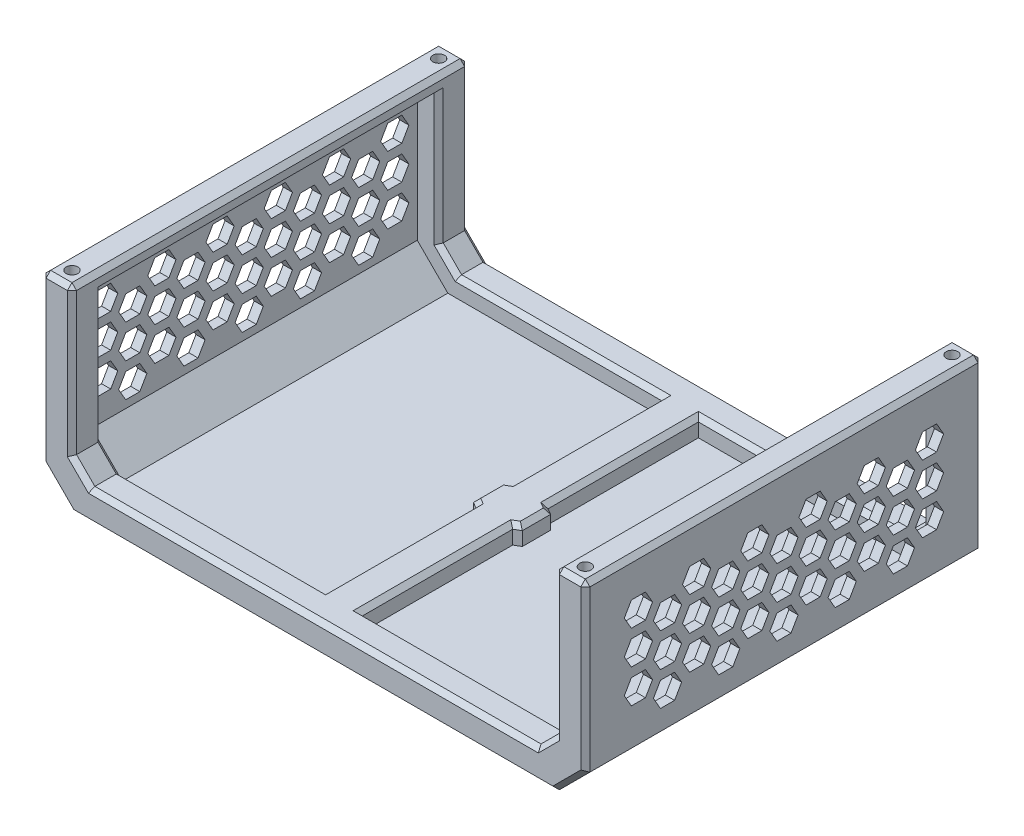
SolidWorks part; units mm, degrees
other "标注1"
sketch "草图16" plane through (-89, 60, 130) normal (-0.0084, 0.3052, 0.9522) x (0.9895, -0.1352, 0.0521)
ref_plane "前视基准面" through (0, 0, 0) normal (0, 0, 1) x (1, 0, 0)
ref_plane "上视基准面" through (0, 0, 0) normal (0, 1, 0) x (1, 0, 0)
ref_plane "右视基准面" through (0, 0, 0) normal (1, 0, 0) x (0, 0, -1)
sketch "草图1" plane through (0, 0, 0) normal (0, 0, 1) x (1, 0, 0)
  line L0 (-86, 0) -> (86, 0)
  line L1 (86, 0) -> (86, 60)
  line L2 (86, 60) -> (89, 60)
  line L3 (89, 60) -> (89, -4)
  line L4 (89, -4) -> (-89, -4)
  line L5 (0, -4) -> (0, 0) construction
  line L6 (-89, 60) -> (-89, -4)
  line L7 (-86, 60) -> (-89, 60)
  line L8 (-86, 0) -> (-86, 60)
  dimension "D1" = 3
  dimension "D2" = 4
  dimension "D3" = 178
  dimension "D4" = 60
extrude "凸台-拉伸2" add sketch "草图1" along normal blind 130
sketch "草图3" plane through (0, 60, 0) normal (0, 1, 0) x (1, 0, 0)
  line L0 (89, -130) -> (86, -130) construction
  line L1 (-79, -10) -> (-89, -10)
  line L2 (-79, -10) -> (-79, 0)
  line L3 (-79, 0) -> (-89, 0)
  line L4 (-89, -10) -> (-89, 0)
  line L5 (-79, -10) -> (-89, 0) construction
  line L6 (-79, 0) -> (-89, -10) construction
  line L7 (79, -10) -> (89, -10)
  line L8 (79, -10) -> (79, 0)
  line L9 (79, 0) -> (89, 0)
  line L10 (89, -10) -> (89, 0)
  line L11 (79, -10) -> (89, 0) construction
  line L12 (79, 0) -> (89, -10) construction
  line L13 (79, -120) -> (89, -120)
  line L14 (79, -120) -> (79, -130)
  line L15 (79, -130) -> (89, -130)
  line L16 (89, -120) -> (89, -130)
  line L17 (79, -120) -> (89, -130) construction
  line L18 (79, -130) -> (89, -120) construction
  line L19 (89, -130) -> (89, 0) construction
  line L21 (-79, -120) -> (-89, -120)
  line L22 (-79, -120) -> (-79, -130)
  line L23 (-79, -130) -> (-89, -130)
  line L24 (-89, -120) -> (-89, -130)
  line L25 (-79, -120) -> (-89, -130) construction
  line L26 (-79, -130) -> (-89, -120) construction
  point P0 (-84, -5)
  point P6 (84, -125)
  point P7 (84, -5)
  point P21 (-84, -125)
  dimension "D1" = 10
  dimension "D2" = 10
  dimension "D3" = 10
  dimension "D4" = 10
  dimension "D5" = 10
  dimension "D6" = 10
  dimension "D7" = 10
  dimension "D8" = 10
extrude "凸台-拉伸3" add sketch "草图3" against normal up to surface (60 mm away) up to face at (0, 0, 65)
sketch "草图4" plane through (0, 60, 0) normal (0, 1, 0) x (1, 0, 0)
  line L0 (-79, 0) -> (-89, 0) construction
  line L1 (-89, -130) -> (-89, 0) construction
  line L2 (89, 0) -> (79, 0) construction
  line L3 (89, -130) -> (89, 0) construction
  line L4 (89, -130) -> (79, -130) construction
  line L5 (-79, -130) -> (-89, -130) construction
  circle A0 centre (-84, -5) radius 1.9
  circle A1 centre (84, -5) radius 1.9
  circle A2 centre (84, -125) radius 1.9
  circle A3 centre (-84, -125) radius 1.9
  dimension "D4" = 5
  dimension "D9" = 3.8
  dimension "D10" = 3.8
  dimension "D11" = 3.8
  dimension "D12" = 3.8
  dimension "D1" = 5
  dimension "D2" = 5
  dimension "D3" = 5
  dimension "D5" = 5
  dimension "D6" = 5
  dimension "D7" = 5
  dimension "D8" = 5
extrude "切除-拉伸1" cut sketch "草图4" against normal blind 8
chamfer "倒角1" distance 10 angle 45 2 edges at (86, 0, 65) (-86, 0, 65)
chamfer "倒角2" distance 10 angle 45 2 edges at (89, -4, 65) (-89, -4, 65)
sketch "草图6" plane through (0, 0, 0) normal (1, 0, 0) x (0, 0, -1)
  line L1 (-120, 6) -> (-130, 6)
  line L2 (-120, 6) -> (-120, -4)
  line L3 (-120, -4) -> (-130, -4)
  line L4 (-130, 6) -> (-130, -4)
  line L5 (-120, 6) -> (-130, -4) construction
  line L6 (-120, -4) -> (-130, 6) construction
  line L7 (-10, 6) -> (0, 6)
  line L8 (-10, 6) -> (-10, -4)
  line L9 (-10, -4) -> (0, -4)
  line L10 (0, 6) -> (0, -4)
  line L11 (-10, 6) -> (0, -4) construction
  line L12 (-10, -4) -> (0, 6) construction
  point P0 (-125, 1)
  point P6 (-5, 1)
  dimension "D1" = 10
  dimension "D2" = 10
  dimension "D3" = 10
  dimension "D4" = 10
extrude "凸台-拉伸4" add sketch "草图6" along normal up to surface and the other way up to surface up to face at (79, 31.5, 125) other way up to face at (-79, 31.5, 125)
chamfer "倒角3" distance 6 angle 45 4 edges at (-79, 6, 5) (79, 6, 5) (79, 6, 125) (-79, 6, 125)
sketch "草图10" plane through (0, 0, 10) normal (0, 0, 1) x (1, 0, 0)
  line L0 (86, 60) -> (79, 60)
  line L1 (79, 60) -> (86, 60) construction
  line L2 (79, 60) -> (79, 55)
  line L3 (79, 12) -> (79, 60) construction
  line L4 (79, 55) -> (86, 50)
  line L5 (86, 60) -> (86, 10) construction
  line L6 (86, 50) -> (86, 60)
  line L7 (-86, 60) -> (-79, 60)
  line L8 (-86, 60) -> (-79, 60) construction
  line L9 (-79, 12) -> (-79, 60) construction
  line L10 (-79, 60) -> (-79, 56)
  line L11 (-79, 56) -> (-86, 50)
  line L12 (-86, 10) -> (-86, 60) construction
  line L13 (-86, 50) -> (-86, 60)
  dimension "D1" = 5
  dimension "D2" = 10
  dimension "D3" = 10
  dimension "D4" = 4
extrude "凸台-拉伸6" add sketch "草图10" along normal up to next
sketch "草图17" plane through (0, 0, 0) normal (0, 1, 0) x (1, 0, 0)
  line L0 (73, -10) -> (-73, -10) construction
  line L1 (-6, -10) -> (6, -10)
  line L2 (-6, -10) -> (-6, -120)
  line L3 (-6, -120) -> (6, -120)
  line L4 (6, -10) -> (6, -120)
  line L5 (73, -120) -> (-73, -120) construction
  line L6 (0, 0) -> (0, -130) construction
  line L7 (73, 0) -> (-73, 0) construction
  line L8 (73, -130) -> (-73, -130) construction
  line L13 (-76, -10) -> (76, -10) construction
  point P14 (4.0636, -10)
  point P17 (0, -10)
  dimension "D1" = 12
extrude "凸台-拉伸7" add sketch "草图17" along normal up to surface (6 mm away) up to face at (0, 6, 5)
sketch "草图20" plane through (0, -4, 0) normal (0, -1, 0) x (-1, 0, 0)
  line L0 (79, -65) -> (-79, -65) construction
  line L1 (79, -130) -> (79, 0) construction
  line L2 (-79, 0) -> (-79, -130) construction
  line L3 (0, 0) -> (0, -130) construction
  line L4 (79, -130) -> (-79, -130) construction
  circle A0 centre (0, -65) radius 3.05
  point P13 (0, 0)
  point P14 (0, -65)
  dimension "D2" = 6.1
extrude "切除-拉伸3" cut sketch "草图20" against normal blind 6.5
sketch "草图21" plane through (0, 6, 0) normal (0, 1, 0) x (1, 0, 0)
  line L1 (0, -55.7624) -> (-8, -60.3812)
  line L2 (-8, -60.3812) -> (-8, -69.6188)
  line L3 (-8, -69.6188) -> (0, -74.2376)
  line L4 (0, -74.2376) -> (8, -69.6188)
  line L5 (8, -69.6188) -> (8, -60.3812)
  line L6 (8, -60.3812) -> (0, -55.7624)
  circle A0 centre (0, -65) radius 8 construction
  circle A2 centre (0, -65) radius 3.05
  circle A4 centre (0, -65) radius 3.05 construction
  circle A6 centre (0, -65) radius 8 construction
  dimension "D1" = 16
extrude "凸台-拉伸9" add sketch "草图21" against normal up to surface (6 mm away) up to face at (41, 0, 65)
sketch "草图22" plane through (89, 0, 0) normal (1, 0, 0) x (0, 0, -1)
  line L0 (-100.6094, 44) -> (-39.7114, 44) construction
  line L1 (-108.0126, 44) -> (-110.322, 48)
  line L2 (-110.322, 48) -> (-114.9408, 48)
  line L3 (-114.9408, 48) -> (-117.2502, 44)
  line L4 (-117.2502, 44) -> (-114.9408, 40)
  line L5 (-114.9408, 40) -> (-110.322, 40)
  line L6 (-110.322, 40) -> (-108.0126, 44)
  line L7 (-130, 60) -> (0, 60) construction
  line L9 (-91.2694, 48) -> (-95.8882, 48)
  line L10 (-95.8882, 48) -> (-98.1976, 44)
  line L11 (-98.1976, 44) -> (-95.8882, 40)
  line L12 (-95.8882, 40) -> (-91.2694, 40)
  line L13 (-91.2694, 40) -> (-88.96, 44)
  line L14 (-88.96, 44) -> (-91.2694, 48)
  line L15 (-81.7432, 42.5) -> (-86.362, 42.5)
  line L16 (-105.2526, 38.5) -> (-89.35, 38.5) construction
  line L17 (-98.4863, 38.5) -> (-100.7957, 42.5)
  line L18 (-100.7957, 42.5) -> (-105.4145, 42.5)
  line L19 (-105.4145, 42.5) -> (-107.7239, 38.5)
  line L20 (-107.7239, 38.5) -> (-105.4145, 34.5)
  line L21 (-105.4145, 34.5) -> (-100.7957, 34.5)
  line L22 (-100.7957, 34.5) -> (-98.4863, 38.5)
  line L23 (-72.2169, 48) -> (-76.8357, 48)
  line L24 (-76.8357, 48) -> (-79.1451, 44)
  line L25 (-79.1451, 44) -> (-76.8357, 40)
  line L26 (-76.8357, 40) -> (-72.2169, 40)
  line L27 (-72.2169, 40) -> (-69.9075, 44)
  line L28 (-69.9075, 44) -> (-72.2169, 48)
  line L29 (-53.1643, 48) -> (-57.7831, 48)
  line L30 (-57.7831, 48) -> (-60.0925, 44)
  line L31 (-60.0925, 44) -> (-57.7831, 40)
  line L32 (-57.7831, 40) -> (-53.1643, 40)
  line L33 (-53.1643, 40) -> (-50.8549, 44)
  line L34 (-50.8549, 44) -> (-53.1643, 48)
  line L35 (-34.1118, 48) -> (-38.7306, 48)
  line L36 (-38.7306, 48) -> (-41.04, 44)
  line L37 (-41.04, 44) -> (-38.7306, 40)
  line L38 (-38.7306, 40) -> (-34.1118, 40)
  line L39 (-34.1118, 40) -> (-31.8024, 44)
  line L40 (-31.8024, 44) -> (-34.1118, 48)
  line L41 (-15.0592, 48) -> (-19.678, 48)
  line L42 (-19.678, 48) -> (-21.9874, 44)
  line L43 (-21.9874, 44) -> (-19.678, 40)
  line L44 (-19.678, 40) -> (-15.0592, 40)
  line L45 (-15.0592, 40) -> (-12.7498, 44)
  line L46 (-12.7498, 44) -> (-15.0592, 48)
  line L47 (-86.362, 42.5) -> (-88.6714, 38.5)
  line L48 (-88.6714, 38.5) -> (-86.362, 34.5)
  line L49 (-86.362, 34.5) -> (-81.7432, 34.5)
  line L50 (-81.7432, 34.5) -> (-79.4338, 38.5)
  line L51 (-79.4338, 38.5) -> (-81.7432, 42.5)
  line L52 (-62.6906, 42.5) -> (-67.3094, 42.5)
  line L53 (-67.3094, 42.5) -> (-69.6188, 38.5)
  line L54 (-69.6188, 38.5) -> (-67.3094, 34.5)
  line L55 (-67.3094, 34.5) -> (-62.6906, 34.5)
  line L56 (-62.6906, 34.5) -> (-60.3812, 38.5)
  line L57 (-60.3812, 38.5) -> (-62.6906, 42.5)
  line L58 (-43.638, 42.5) -> (-48.2568, 42.5)
  line L59 (-48.2568, 42.5) -> (-50.5662, 38.5)
  line L60 (-50.5662, 38.5) -> (-48.2568, 34.5)
  line L61 (-48.2568, 34.5) -> (-43.638, 34.5)
  line L62 (-43.638, 34.5) -> (-41.3286, 38.5)
  line L63 (-41.3286, 38.5) -> (-43.638, 42.5)
  line L64 (-24.5855, 42.5) -> (-29.2043, 42.5)
  line L65 (-29.2043, 42.5) -> (-31.5137, 38.5)
  line L66 (-31.5137, 38.5) -> (-29.2043, 34.5)
  line L67 (-29.2043, 34.5) -> (-24.5855, 34.5)
  line L68 (-24.5855, 34.5) -> (-22.2761, 38.5)
  line L69 (-22.2761, 38.5) -> (-24.5855, 42.5)
  line L70 (-112.6314, 44) -> (-112.6314, 13.0061) construction
  line L71 (-108.0126, 33) -> (-110.322, 37)
  line L72 (-110.322, 37) -> (-114.9408, 37)
  line L73 (-114.9408, 37) -> (-117.2502, 33)
  line L74 (-117.2502, 33) -> (-114.9408, 29)
  line L75 (-114.9408, 29) -> (-110.322, 29)
  line L76 (-110.322, 29) -> (-108.0126, 33)
  line L77 (-91.2694, 37) -> (-95.8882, 37)
  line L78 (-95.8882, 37) -> (-98.1976, 33)
  line L79 (-98.1976, 33) -> (-95.8882, 29)
  line L80 (-95.8882, 29) -> (-91.2694, 29)
  line L81 (-91.2694, 29) -> (-88.96, 33)
  line L82 (-88.96, 33) -> (-91.2694, 37)
  line L83 (-81.7432, 31.5) -> (-86.362, 31.5)
  line L84 (-98.4863, 27.5) -> (-100.7957, 31.5)
  line L85 (-100.7957, 31.5) -> (-105.4145, 31.5)
  line L86 (-105.4145, 31.5) -> (-107.7239, 27.5)
  line L87 (-107.7239, 27.5) -> (-105.4145, 23.5)
  line L88 (-105.4145, 23.5) -> (-100.7957, 23.5)
  line L89 (-100.7957, 23.5) -> (-98.4863, 27.5)
  line L90 (-72.2169, 37) -> (-76.8357, 37)
  line L91 (-76.8357, 37) -> (-79.1451, 33)
  line L92 (-79.1451, 33) -> (-76.8357, 29)
  line L93 (-76.8357, 29) -> (-72.2169, 29)
  line L94 (-72.2169, 29) -> (-69.9075, 33)
  line L95 (-69.9075, 33) -> (-72.2169, 37)
  line L96 (-53.1643, 37) -> (-57.7831, 37)
  line L97 (-57.7831, 37) -> (-60.0925, 33)
  line L98 (-60.0925, 33) -> (-57.7831, 29)
  line L99 (-57.7831, 29) -> (-53.1643, 29)
  line L100 (-53.1643, 29) -> (-50.8549, 33)
  line L101 (-50.8549, 33) -> (-53.1643, 37)
  line L102 (-34.1118, 37) -> (-38.7306, 37)
  line L103 (-38.7306, 37) -> (-41.04, 33)
  line L104 (-41.04, 33) -> (-38.7306, 29)
  line L105 (-38.7306, 29) -> (-34.1118, 29)
  line L106 (-34.1118, 29) -> (-31.8024, 33)
  line L107 (-31.8024, 33) -> (-34.1118, 37)
  line L108 (-15.0592, 37) -> (-19.678, 37)
  line L109 (-19.678, 37) -> (-21.9874, 33)
  line L110 (-21.9874, 33) -> (-19.678, 29)
  line L111 (-19.678, 29) -> (-15.0592, 29)
  line L112 (-15.0592, 29) -> (-12.7498, 33)
  line L113 (-12.7498, 33) -> (-15.0592, 37)
  line L114 (-86.362, 31.5) -> (-88.6714, 27.5)
  line L115 (-88.6714, 27.5) -> (-86.362, 23.5)
  line L116 (-86.362, 23.5) -> (-81.7432, 23.5)
  line L117 (-81.7432, 23.5) -> (-79.4338, 27.5)
  line L118 (-79.4338, 27.5) -> (-81.7432, 31.5)
  line L119 (-62.6906, 31.5) -> (-67.3094, 31.5)
  line L120 (-67.3094, 31.5) -> (-69.6188, 27.5)
  line L121 (-69.6188, 27.5) -> (-67.3094, 23.5)
  line L122 (-67.3094, 23.5) -> (-62.6906, 23.5)
  line L123 (-62.6906, 23.5) -> (-60.3812, 27.5)
  line L124 (-60.3812, 27.5) -> (-62.6906, 31.5)
  line L125 (-43.638, 31.5) -> (-48.2568, 31.5)
  line L126 (-48.2568, 31.5) -> (-50.5662, 27.5)
  line L127 (-50.5662, 27.5) -> (-48.2568, 23.5)
  line L128 (-48.2568, 23.5) -> (-43.638, 23.5)
  line L129 (-43.638, 23.5) -> (-41.3286, 27.5)
  line L130 (-41.3286, 27.5) -> (-43.638, 31.5)
  line L131 (-24.5855, 31.5) -> (-29.2043, 31.5)
  line L132 (-29.2043, 31.5) -> (-31.5137, 27.5)
  line L133 (-31.5137, 27.5) -> (-29.2043, 23.5)
  line L134 (-29.2043, 23.5) -> (-24.5855, 23.5)
  line L135 (-24.5855, 23.5) -> (-22.2761, 27.5)
  line L136 (-22.2761, 27.5) -> (-24.5855, 31.5)
  line L137 (-108.0126, 22) -> (-110.322, 26)
  line L138 (-110.322, 26) -> (-114.9408, 26)
  line L139 (-114.9408, 26) -> (-117.2502, 22)
  line L140 (-117.2502, 22) -> (-114.9408, 18)
  line L141 (-114.9408, 18) -> (-110.322, 18)
  line L142 (-110.322, 18) -> (-108.0126, 22)
  line L143 (-91.2694, 26) -> (-95.8882, 26)
  line L144 (-95.8882, 26) -> (-98.1976, 22)
  line L145 (-98.1976, 22) -> (-95.8882, 18)
  line L146 (-95.8882, 18) -> (-91.2694, 18)
  line L147 (-91.2694, 18) -> (-88.96, 22)
  line L148 (-88.96, 22) -> (-91.2694, 26)
  line L149 (-81.7432, 20.5) -> (-86.362, 20.5)
  line L150 (-98.4863, 16.5) -> (-100.7957, 20.5)
  line L151 (-100.7957, 20.5) -> (-105.4145, 20.5)
  line L152 (-105.4145, 20.5) -> (-107.7239, 16.5)
  line L153 (-107.7239, 16.5) -> (-105.4145, 12.5)
  line L154 (-105.4145, 12.5) -> (-100.7957, 12.5)
  line L155 (-100.7957, 12.5) -> (-98.4863, 16.5)
  line L156 (-72.2169, 26) -> (-76.8357, 26)
  line L157 (-76.8357, 26) -> (-79.1451, 22)
  line L158 (-79.1451, 22) -> (-76.8357, 18)
  line L159 (-76.8357, 18) -> (-72.2169, 18)
  line L160 (-72.2169, 18) -> (-69.9075, 22)
  line L161 (-69.9075, 22) -> (-72.2169, 26)
  line L162 (-53.1643, 26) -> (-57.7831, 26)
  line L163 (-57.7831, 26) -> (-60.0925, 22)
  line L164 (-60.0925, 22) -> (-57.7831, 18)
  line L165 (-57.7831, 18) -> (-53.1643, 18)
  line L166 (-53.1643, 18) -> (-50.8549, 22)
  line L167 (-50.8549, 22) -> (-53.1643, 26)
  line L168 (-34.1118, 26) -> (-38.7306, 26)
  line L169 (-38.7306, 26) -> (-41.04, 22)
  line L170 (-41.04, 22) -> (-38.7306, 18)
  line L171 (-38.7306, 18) -> (-34.1118, 18)
  line L172 (-34.1118, 18) -> (-31.8024, 22)
  line L173 (-31.8024, 22) -> (-34.1118, 26)
  line L174 (-15.0592, 26) -> (-19.678, 26)
  line L175 (-19.678, 26) -> (-21.9874, 22)
  line L176 (-21.9874, 22) -> (-19.678, 18)
  line L177 (-19.678, 18) -> (-15.0592, 18)
  line L178 (-15.0592, 18) -> (-12.7498, 22)
  line L179 (-12.7498, 22) -> (-15.0592, 26)
  line L180 (-86.362, 20.5) -> (-88.6714, 16.5)
  line L181 (-88.6714, 16.5) -> (-86.362, 12.5)
  line L182 (-86.362, 12.5) -> (-81.7432, 12.5)
  line L183 (-81.7432, 12.5) -> (-79.4338, 16.5)
  line L184 (-79.4338, 16.5) -> (-81.7432, 20.5)
  line L185 (-62.6906, 20.5) -> (-67.3094, 20.5)
  line L186 (-67.3094, 20.5) -> (-69.6188, 16.5)
  line L187 (-69.6188, 16.5) -> (-67.3094, 12.5)
  line L188 (-67.3094, 12.5) -> (-62.6906, 12.5)
  line L189 (-62.6906, 12.5) -> (-60.3812, 16.5)
  line L190 (-60.3812, 16.5) -> (-62.6906, 20.5)
  line L191 (-43.638, 20.5) -> (-48.2568, 20.5)
  line L192 (-48.2568, 20.5) -> (-50.5662, 16.5)
  line L193 (-50.5662, 16.5) -> (-48.2568, 12.5)
  line L194 (-48.2568, 12.5) -> (-43.638, 12.5)
  line L195 (-43.638, 12.5) -> (-41.3286, 16.5)
  line L196 (-41.3286, 16.5) -> (-43.638, 20.5)
  line L197 (-24.5855, 20.5) -> (-29.2043, 20.5)
  line L198 (-29.2043, 20.5) -> (-31.5137, 16.5)
  line L199 (-31.5137, 16.5) -> (-29.2043, 12.5)
  line L200 (-29.2043, 12.5) -> (-24.5855, 12.5)
  line L201 (-24.5855, 12.5) -> (-22.2761, 16.5)
  line L202 (-22.2761, 16.5) -> (-24.5855, 20.5)
  line L203 (-65, 60) -> (-65, 6) construction
  line L204 (-130, 6) -> (0, 6) construction
  circle A0 centre (-112.6314, 44) radius 4 construction
  circle A1 centre (-93.5788, 44) radius 4 construction
  circle A2 centre (-103.1051, 38.5) radius 4 construction
  circle A3 centre (-74.5263, 44) radius 4 construction
  circle A4 centre (-55.4737, 44) radius 4 construction
  circle A5 centre (-36.4212, 44) radius 4 construction
  circle A6 centre (-17.3686, 44) radius 4 construction
  circle A7 centre (-84.0526, 38.5) radius 4 construction
  circle A8 centre (-65, 38.5) radius 4 construction
  circle A9 centre (-45.9474, 38.5) radius 4 construction
  circle A10 centre (-26.8949, 38.5) radius 4 construction
  circle A11 centre (-112.6314, 33) radius 4 construction
  circle A12 centre (-93.5788, 33) radius 4 construction
  circle A13 centre (-103.1051, 27.5) radius 4 construction
  circle A14 centre (-74.5263, 33) radius 4 construction
  circle A15 centre (-55.4737, 33) radius 4 construction
  circle A16 centre (-36.4212, 33) radius 4 construction
  circle A17 centre (-17.3686, 33) radius 4 construction
  circle A18 centre (-84.0526, 27.5) radius 4 construction
  circle A19 centre (-65, 27.5) radius 4 construction
  circle A20 centre (-45.9474, 27.5) radius 4 construction
  circle A21 centre (-26.8949, 27.5) radius 4 construction
  circle A22 centre (-112.6314, 22) radius 4 construction
  circle A23 centre (-93.5788, 22) radius 4 construction
  circle A24 centre (-103.1051, 16.5) radius 4 construction
  circle A25 centre (-74.5263, 22) radius 4 construction
  circle A26 centre (-55.4737, 22) radius 4 construction
  circle A27 centre (-36.4212, 22) radius 4 construction
  circle A28 centre (-17.3686, 22) radius 4 construction
  circle A29 centre (-84.0526, 16.5) radius 4 construction
  circle A30 centre (-65, 16.5) radius 4 construction
  circle A31 centre (-45.9474, 16.5) radius 4 construction
  circle A32 centre (-26.8949, 16.5) radius 4 construction
  point P98 (-90.1147, 42)
  dimension "D1" = 8
  dimension "D5" = 8
  dimension "D2" = 16
  dimension "D6" = 3
  dimension "D7" = 3
  dimension "D8" = 1.5
  dimension "D9" = 5
  dimension "D10" = 3
  dimension "D11" = 3
  dimension "D12" = 11
  dimension "D4" = 6
extrude "切除-拉伸5" cut sketch "草图22" against normal through all
chamfer "倒角4" distance 1.5 angle 45 28 edges at (89, 60, 65) (79, 60, 65) (-89, 60, 65) (89, 33, 0) (84, 60, 0) (79, 36, 0) (76, 9, 0) (0, 6, 0) (-76, 9, 0) (-79, 36, 0) (84, 1, 0) (0, -4, 0) (-84, 1, 0) (-89, 33, 0) (-84, 60, 0) (-79, 60, 65) (-89, 33, 130) (-84, 60, 130) (-79, 36, 130) (-76, 9, 130) (0, 6, 130) (76, 9, 130) (79, 36, 130) (84, 60, 130) (89, 33, 130) (84, 1, 130) (0, -4, 130) (-84, 1, 130)
chamfer "倒角6" distance 1.5 angle 45 11 edges at (-79, 34, 10) (-79, 34, 120) (-76, 9, 10) (-76, 9, 120) (-39.5, 6, 10) (-39.5, 6, 120) (-6, 6, 95.3868) (-6, 6, 34.6132) (-7, 6, 59.8038) (-8, 6, 65) (-7, 6, 70.1962)
chamfer "倒角7" distance 1.5 angle 45 11 edges at (79, 33.5, 120) (76, 9, 120) (39.5, 6, 120) (39.5, 6, 10) (76, 9, 10) (79, 33.5, 10) (6, 6, 95.3868) (7, 6, 70.1962) (8, 6, 65) (7, 6, 59.8038) (6, 6, 34.6132)
chamfer "倒角8" distance 1 angle 45 1 edges at (0, -4, 61.95)
